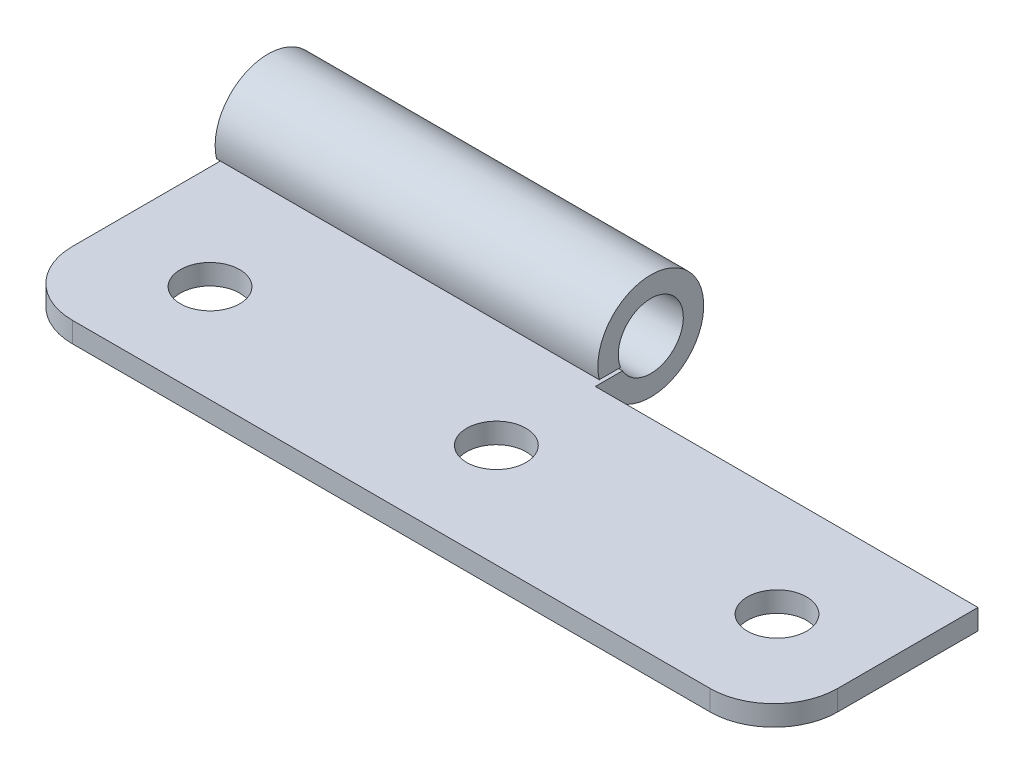
SolidWorks part; units mm, degrees
material "Нержавеющая сталь (ферритная)"
ref_plane "Спереди" through (0, 0, 0) normal (0, 0, 1) x (1, 0, 0)
ref_plane "Сверху" through (0, 0, 0) normal (0, 1, 0) x (1, 0, 0)
ref_plane "Справа" through (0, 0, 0) normal (1, 0, 0) x (0, 0, -1)
sketch "Эскиз1" plane through (0, 0, 0) normal (1, 0, 0) x (0, 0, -1)
  circle A0 centre (0, 0) radius 4.15
  dimension "D1" = 8.3
extrude "Бобышка-Вытянуть1" add sketch "Эскиз1" along normal blind 60
ref_plane "Плоскость1" through (0, -2.85, 0) normal (0, 1, 0) x (1, 0, 0)
sketch "Эскиз2" plane through (0, -2.85, 0) normal (0, 1, 0) x (1, 0, 0)
  line L0 (60, 4.15) -> (0, 4.15) construction
  line L1 (0, -4.15) -> (60, -4.15) construction
  line L2 (0, -4.15) -> (0, -20.35)
  line L3 (0, -20.35) -> (60, -20.35)
  line L4 (60, -4.15) -> (60, -20.35)
  line L5 (60, 4.15) -> (0, 4.15) construction
  line L6 (0, -4.15) -> (0, 0)
  line L7 (0, 0) -> (60, 0)
  line L8 (60, 0) -> (60, -4.15)
  line L9 (5.8, -12.675) -> (0, -12.675) construction
  line L10 (0, -4.35) -> (60, -4.35) construction
  line L11 (0, -4.35) -> (0, -20.35) construction
  line L12 (0, -20.35) -> (60, -20.35) construction
  line L13 (60, -4.35) -> (60, -20.35) construction
  line L14 (0, -4.35) -> (60, -20.35) construction
  line L15 (0, -20.35) -> (60, -4.35) construction
  line L16 (8.125, -10.35) -> (8.125, -4.35) construction
  line L17 (8.125, -15) -> (8.125, -20.35) construction
  line L18 (30.1192, -14.55) -> (30.1192, -20.35) construction
  circle A0 centre (8.125, -12.675) radius 2.325
  circle A1 centre (30.1192, -12.225) radius 2.325
  circle A2 centre (52.5692, -12.675) radius 2.325
  point P8 (30, -12.35)
  point P21 (10.45, -12.675)
  point P25 (27.7942, -12.225)
  point P27 (50.2442, -12.675)
  point P28 (32.4442, -12.225)
  point P32 (54.8942, -12.675)
  dimension "D3" = 4.65
  dimension "D1" = 16
  dimension "D2" = 60
  dimension "D4" = 6
  dimension "D5" = 5.8
  dimension "D6" = 17.35
  dimension "D7" = 5.8
  dimension "D8" = 27.1
  dimension "D9" = 0
  dimension "D10" = 24.5
extrude "Бобышка-Вытянуть2" add sketch "Эскиз2" along normal blind 1.6
sketch "Эскиз3" plane through (60, 0, 0) normal (1, 0, 0) x (0, 0, -1)
  line L0 (0, -4.15) -> (-5.0015, -4.15)
  line L2 (-20.35, -2.85) -> (-3.0166, -2.85) construction
  line L3 (0, 0) -> (0, -4.15) construction
  arc A1 (-3.0166, -2.85) -> (-3.9573, -1.25) centre (0, 0) ccw construction
  dimension "D1" = 1.3
fillet "Скругление1" radius 5 2 edges at (60, -2.05, 20.35) (0, -2.05, 20.35)
sketch "Эскиз5" plane through (0, 0, 0) normal (-1, 0, 0) x (0, 0, 1)
  line L0 (3.9573, -1.25) -> (2.2226, -1.25)
  line L1 (4.0398, -0.95) -> (2.3664, -0.95)
  line L2 (3.9573, -1.25) -> (4.0398, -1.25)
  line L3 (3.9573, -1.25) -> (15.35, -1.25) construction
  line L4 (4.0398, -1.25) -> (4.0398, -0.95)
  arc A0 (2.3664, -0.95) -> (2.2226, -1.25) centre (0, 0) ccw
  arc A1 (3.9573, -1.25) -> (3.0166, -2.85) centre (0, 0) ccw construction
  dimension "D1" = 5.1
  dimension "D3" = 1.6
  dimension "D2" = 0.3
extrude "Вырез-Вытянуть2" cut sketch "Эскиз5" against normal through all
sketch "Эскиз4" plane through (0, -1.25, 0) normal (0, 1, 0) x (1, 0, 0)
  line L0 (60, 4.15) -> (0, 4.15) construction
  line L6 (30, 4.15) -> (60, 4.15)
  line L7 (30, 4.15) -> (30, -4.35)
  line L8 (30, -4.35) -> (60, -4.35)
  line L9 (60, 4.15) -> (60, -4.35)
  line L11 (60, 0) -> (60, -5.0015) construction
  line L12 (5, -20.35) -> (55, -20.35) construction
  line L13 (0, 4.15) -> (0, -4.15) construction
  dimension "D1" = 16
  dimension "D2" = 30
extrude "Вырез-Вытянуть1" cut sketch "Эскиз4" against normal through all and the other way through all
